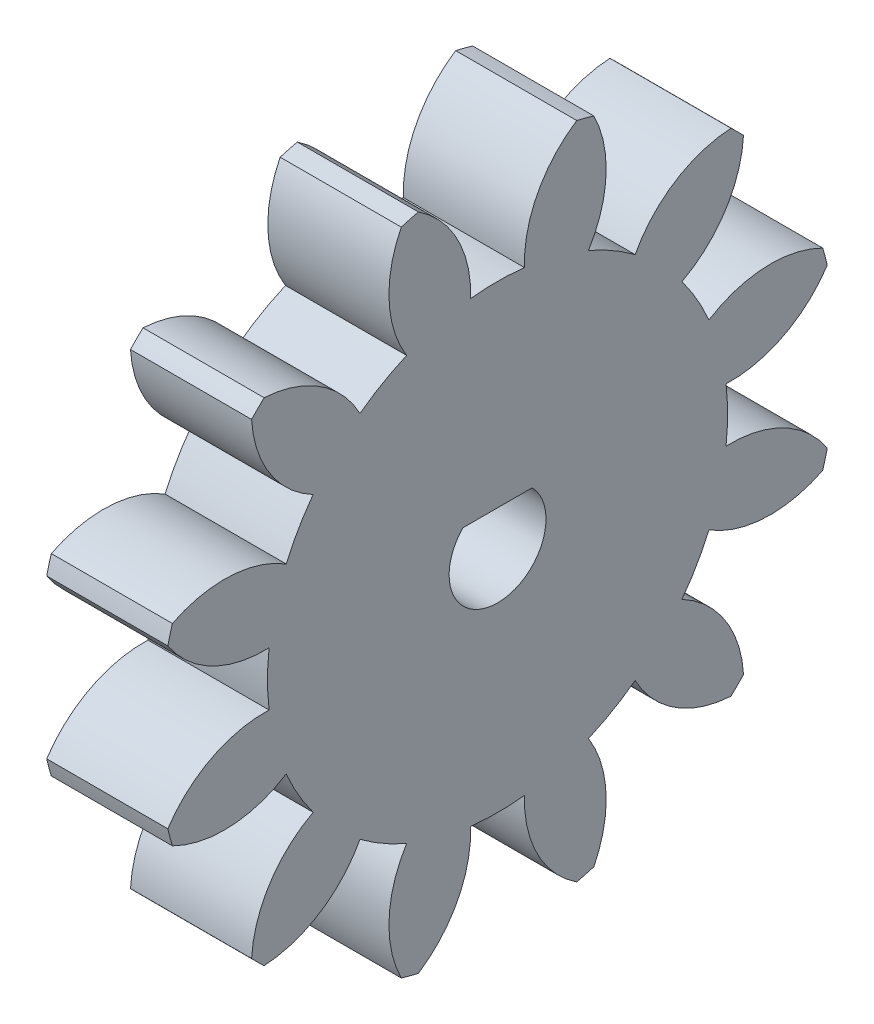
SolidWorks part; units mm, degrees
ref_plane "Plane1" through (0, 0, 0) normal (0, 0, 1) x (1, 0, 0)
ref_plane "Plane2" through (0, 0, 0) normal (0, 1, 0) x (1, 0, 0)
ref_plane "Plane3" through (0, 0, 0) normal (1, 0, 0) x (0, 0, -1)
sketch "HoldingSke" plane through (0, 0, 0) normal (0, 1, 0) x (1, 0, 0)
  line L0 (0, 0) -> (0.4891, -0.104)
  line L1 (-15, 0) -> (100, 0) construction
  line L2 (0, 0) -> (-2.1039, 2.3779)
  line L3 (0, 0) -> (-11.863, 4.5341)
  line L4 (0, 0) -> (8.4473, 1.7955)
  line L5 (0, 0) -> (-46.8476, -17.4728)
  line L6 (0, 0) -> (-4.1448, -2.7965)
  line L7 (-2.1039, 2.3779) -> (8.6586, 51.2059)
  line L8 (-76.2, 54.61) -> (-75.5, 54.61)
  line L9 (-71.009, 38.7566) -> (-53.1078, 45.2721)
  line L10 (-76.2, 71.12) -> (104.1128, 71.12)
  line L11 (0, 0) -> (-5, 0)
  line L12 (-76.2, 101.6) -> (-76.133, 101.6)
  line L13 (24.9733, 27.94) -> (52.9518, 28.4284)
  line L14 (24.9733, 27.94) -> (24.9743, 27.94)
  line L15 (24.9733, 27.94) -> (100.4006, 29.5858)
  line L16 (-63.627, -2) -> (-12.827, -2)
  circle A0 centre (0, 0) radius 2
  circle A1 centre (0, 0) radius 9.499
  circle A2 centre (0, 0) radius 37.5
  circle A3 centre (0, 0) radius 2
  dimension "MHD" = 18.998
  dimension "Hub_dia" = 75
  dimension "Bore" = 4
  dimension "MBD" = 4
  dimension "Num_teeth" = 12
  dimension "Pitch" = 0.5
  dimension "Overall_len" = 50
  dimension "Show_teeth" = 12
  dimension "Thickness" = 5
  dimension "OAL" = 50.0001
  dimension "T_dim" = 0.7
  dimension "Ap" = 20
  dimension "H" = 19.05
  dimension "Pitch_radius" = 180.3128
  dimension "Width" = 5
  dimension "Backlash" = 0.067
  dimension "Addendum_fac" = 1
  dimension "Dedendum_fac" = 1.25
  dimension "Clearance_fac" = 0.25
  dimension "Dedendum_add" = 0.001
  dimension "Module" = 2
sketch "BasProSke" plane through (0, 0, 0) normal (0, 1, 0) x (1, 0, 0)
  line L0 (-10, 0) -> (60, 0) construction
  line L1 (0, 0) -> (0, 14)
  line L2 (0, 0) -> (5, 0)
  line L3 (5, 0) -> (5, 14)
  line L4 (5, 14) -> (0, 14)
  dimension "Thickness" = 5
  dimension "Diameter" = 28
revolve "Base-Revolve" add sketch "BasProSke" angle 360 about L0
sketch "TooCutSke" plane through (0, 0, 0) normal (1, 0, 0) x (0, 0, -1)
  line L1 (0, 0) -> (0, 107) construction
  line L2 (0, 0) -> (-1.6834, 11.8813) construction
  line L3 (0, 0) -> (-6.1662, 23.0126) construction
  line L4 (-1.6834, 11.8813) -> (-3.0831, 11.5063) construction
  arc A0 (1.1119, 9.4337) -> (-1.1119, 9.4337) centre (0, 0) ccw
  arc A1 (3.2981, 13.6321) -> (-3.2981, 13.6321) centre (0, 0) ccw
  circle A2 centre (0, 0) radius 12 construction
  circle A3 centre (0, 0) radius 11.2763 construction
  arc A4 (-1.1119, 9.4337) -> (-3.2981, 13.6321) centre (-5.9089, 9.6042) ccw
  arc A5 (3.2981, 13.6321) -> (1.1119, 9.4337) centre (5.9089, 9.6042) ccw
  dimension "Root_dia" = 18.998
  dimension "Overcut_dia" = 28.0508
  dimension "Pitch_dia" = 24
  dimension "Base_dia" = 22.5526
  dimension "Flank_rad" = 4.8
  dimension "Half_ang" = 15
  dimension "Half_CT" = 1.4491
extrude "ToothCut" cut sketch "TooCutSke" along normal through all
fillet "Breaks" [suppressed] radius 0.04
fillet "RootFillets" [suppressed] radius 0.501
pattern_circular "TeethCuts" count 12 every 30 about axis through (-10, 0, 0) along (1, 0, 0) of "ToothCut", "RootFillets", "Breaks"
sketch "HubNeaOneSke" plane through (0, 0, 0) normal (-1, 0, 0) x (0, 0, 1)
  circle A0 centre (0, 0) radius 9.499
  dimension "Diameter" = 18.998
extrude "HubNearOne" [suppressed] add sketch "HubNeaOneSke" along normal blind 45.0001
sketch "HubNeaBotSke" plane through (0, 0, 0) normal (-1, 0, 0) x (0, 0, 1)
  circle A0 centre (0, 0) radius 9.499
  dimension "Diameter" = 18.998
extrude "HubNearBoth" [suppressed] add sketch "HubNeaBotSke" along normal blind 22.5
ref_plane "FarPln" through (5, 0, 0) normal (1, 0, 0) x (0, 0, -1)
sketch "HubFarSke" plane through (5, 0, 0) normal (1, 0, 0) x (0, 0, -1)
  circle A0 centre (0, 0) radius 9.499
  dimension "Diameter" = 18.998
extrude "HubFar" [suppressed] add sketch "HubFarSke" along normal blind 22.5
sketch "BorSke" plane through (0, 0, 0) normal (1, 0, 0) x (0, 0, -1)
  circle A0 centre (0, 0) radius 2
  dimension "Diameter" = 4
extrude "Bore" cut sketch "BorSke" along normal mid plane 100.0001
sketch "KeySke" plane through (0, 0, 0) normal (1, 0, 0) x (0, 0, -1)
  line L0 (-0.8, 0) -> (-0.8, 2.7)
  line L1 (-0.8, 2.7) -> (0.8, 2.7)
  line L2 (0.8, 2.7) -> (0.8, 0)
  line L3 (0, 0) -> (0, 34) construction
  line L4 (-0.8, 0) -> (0.8, 0)
  dimension "Offset" = 2.7
  dimension "Width" = 1.6
extrude "Keyway" [suppressed] cut sketch "KeySke" along normal mid plane 100.0001
pattern_circular "Keyway2" [suppressed] count 2 every 90 about axis through (-10, 0, 0) along (1, 0, 0)
sketch "Sketch2" plane through (5, 0, 0) normal (1, 0, 0) x (0, 0, -1)
  line L0 (-1.4283, 1.4) -> (1.4283, 1.4)
  circle A0 centre (0, 0) radius 2 construction
  arc A1 (1.4283, 1.4) -> (-1.4283, 1.4) centre (0, 0) ccw
  dimension "D1" = 1.4
extrude "Boss-Extrude1" add sketch "Sketch2" against normal blind 5
equation "' \"Module@HoldingSke\" = 6.35"
equation "' \"Num_teeth@HoldingSke\" = 12"
equation "' \"Ap@HoldingSke\" =  20"
equation "' \"Ap@HoldingSke\" = 20"
equation "' \"Width@HoldingSke\" = 0.5 * 25.4"
equation "' \"Hub_dia@HoldingSke\"= 1 * 25.4"
equation "' \"Hub_dia@HoldingSke\" = 1 * 25.4"
equation "' \"Overall_len@HoldingSke\" = 1.0 * 25.4"
equation "' \"Bore@HoldingSke\" = 0.75 * 25.4"
equation "' \"T_dim@HoldingSke\" = 0.1 * 25.4"
equation "' \"Width@KeySke\" = 0.25 * 25.4"
equation "' \"Show_teeth@HoldingSke\" = 13"
equation "' \"Backlash@HoldingSke\" = 0.009 * 25.4"
equation "' \"Addendum_fac@HoldingSke\" = 1.0"
equation "' \"Dedendum_fac@HoldingSke\" = 1.25"
equation "' \"Dedendum_add@HoldingSke\" = 0.00005 * 25.4"
equation "' \"Clearance_fac@HoldingSke\" = 0.25"
equation "\"Pitch@HoldingSke\" = 1 / \"Module@HoldingSke\""
equation "\"Overcut_dia@TooCutSke\" = (\"Num_teeth@HoldingSke\" + 2 * \"Addendum_fac@HoldingSke\") / \"Pitch@HoldingSke\" + 0.002 * 25.4"
equation "\"Pitch_dia@TooCutSke\" = \"Num_teeth@HoldingSke\" / \"Pitch@HoldingSke\""
equation "\"Base_dia@TooCutSke\" = \"Num_teeth@HoldingSke\" / \"Pitch@HoldingSke\" * cos((\"Ap@HoldingSke\"  * 3.14159265 / 180))"
equation "\"Root_dia@TooCutSke\" = (\"Num_teeth@HoldingSke\" + 2) / \"Pitch@HoldingSke\" - 2 * (\"Addendum_fac@HoldingSke\" + \"Dedendum_fac@HoldingSke\") / \"Pitch@HoldingSke\" - \"Dedendum_add@HoldingSke\" * 2"
equation "\"Half_ang@TooCutSke\" = 180 / \"Num_teeth@HoldingSke\""
equation "\"Half_CT@TooCutSke\" = \"Num_teeth@HoldingSke\" / \"Pitch@HoldingSke\" * sin((3.14159265 / 2 / \"Num_teeth@HoldingSke\")) / 2 - 7 * \"Backlash@HoldingSke\" / 4"
equation "\"Flank_rad@TooCutSke\" = \"Num_teeth@HoldingSke\" / \"Pitch@HoldingSke\" / 5"
equation "\"Radius@RootFillets\" = \"Clearance_fac@HoldingSke\" / \"Pitch@HoldingSke\" + \"Dedendum_add@HoldingSke\""
equation "\"Break_rad@Breaks\" = 0.02 / \"Pitch@HoldingSke\""
equation "\"Thickness@HoldingSke\" = \"Width@HoldingSke\""
equation "\"OAL@HoldingSke\" = \"Thickness@HoldingSke\""
equation "\"MHD@HoldingSke\" = (\"Num_teeth@HoldingSke\" + 2) / \"Pitch@HoldingSke\" - 2 * (\"Addendum_fac@HoldingSke\" + \"Dedendum_fac@HoldingSke\")  / \"Pitch@HoldingSke\" - \"Dedendum_add@HoldingSke\" * 2"
equation "\"MBD@HoldingSke\" = (\"Num_teeth@HoldingSke\" + 2) / \"Pitch@HoldingSke\" - 2 * (\"Addendum_fac@HoldingSke\" + \"Dedendum_fac@HoldingSke\")  / \"Pitch@HoldingSke\" - \"Dedendum_add@HoldingSke\" * 2 - 0.002 * 25.4"
equation "\"MHD@HoldingSke\" = ((sgn( \"MHD@HoldingSke\" - \"Hub_dia@HoldingSke\" )-1)*( \"MHD@HoldingSke\" - \"Hub_dia@HoldingSke\" ))/-2+ \"Hub_dia@HoldingSke\""
equation "\"MBD@HoldingSke\" = ((sgn( \"MBD@HoldingSke\" - \"Bore@HoldingSke\" )-1)*( \"MBD@HoldingSke\" - \"Bore@HoldingSke\" ))/-2+ \"Bore@HoldingSke\""
equation "\"OAL@HoldingSke\" = ((sgn( \"OAL@HoldingSke\" - \"Overall_len@HoldingSke\" )+1)*( \"OAL@HoldingSke\" - \"Overall_len@HoldingSke\" ))/2 + \"Overall_len@HoldingSke\" + 0.000002 * 25.4"
equation "\"Num_teeth@TeethCuts\" = int( \"Show_teeth@HoldingSke\" ) + 1"
equation "\"Num_teeth@TeethCuts\" = ((sgn( \"Num_teeth@TeethCuts\" - \"Num_teeth@HoldingSke\" )-1)*( \"Num_teeth@TeethCuts\" - \"Num_teeth@HoldingSke\" ))/-2+ \"Num_teeth@HoldingSke\""
equation "\"Num_teeth@TeethCuts\" = ((sgn( \"Num_teeth@TeethCuts\" - 2.0)+1)*( \"Num_teeth@TeethCuts\" - 2.0))/2 +2.0"
equation "\"Angle@TeethCuts\" = 360.0 / \"Num_teeth@HoldingSke\""
equation "\"Diameter@BasProSke\" = (\"Num_teeth@HoldingSke\" + 2 * \"Addendum_fac@HoldingSke\") / \"Pitch@HoldingSke\""
equation "\"Thickness@BasProSke\"  = \"Thickness@HoldingSke\""
equation "' \"Fillet_rad@BasProSke\" =  \"Thickness@HoldingSke\" * 0.05"
equation "' \"Fillet_rad@BasProSke\" = \"Thickness@HoldingSke\" * 0.05"
equation "\"MHD@HoldingSke\" = ((sgn( \"MHD@HoldingSke\" - \"Root_dia@TooCutSke\" )-1)*( \"MHD@HoldingSke\" - \"Root_dia@TooCutSke\" ))/-2+ \"Root_dia@TooCutSke\""
equation "\"Diameter@HubNeaOneSke\" = \"MHD@HoldingSke\""
equation "\"Length@HubNearOne\" = \"OAL@HoldingSke\" - \"Thickness@BasProSke\""
equation "\"Diameter@HubNeaBotSke\" = \"MHD@HoldingSke\""
equation "\"Length@HubNearBoth\" = ( \"OAL@HoldingSke\" - \"Thickness@BasProSke\" ) / 2.0"
equation "\"Thickness@FarPln\" = \"Thickness@BasProSke\""
equation "\"Diameter@HubFarSke\" = \"MHD@HoldingSke\""
equation "\"Length@HubFar\" = ( \"OAL@HoldingSke\" - \"Thickness@BasProSke\" ) / 2.0"
equation "\"Diameter@BorSke\" = \"MBD@HoldingSke\""
equation "\"D1@Bore\" = \"OAL@HoldingSke\" * 2.0"
equation "\"D1@Keyway\" = \"OAL@HoldingSke\" * 2.0"
equation "\"Offset@KeySke\" = \"T_dim@HoldingSke\" + \"MBD@HoldingSke\" / 2.0"
